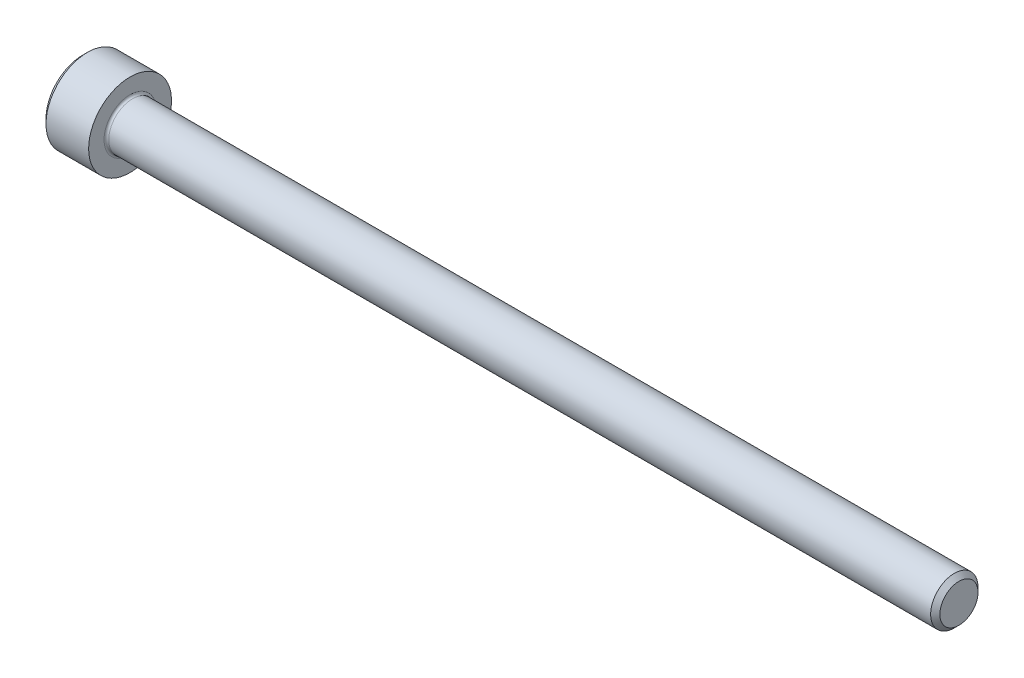
SolidWorks part; units mm, degrees
revolve "Base-Revolve" add sketch "BodySke"
sketch "BodySke" plane through (0, 0, 0) normal (0, 0, 1) x (1, 0, 0)
  line L0 (0, 0) -> (0, 3.1)
  line L1 (0.4, 3.5) -> (4, 3.5)
  line L2 (4, 3.5) -> (4, 2)
  line L3 (4, 2) -> (73.61, 2)
  line L4 (74, 1.61) -> (74, 0)
  line L5 (74, 0) -> (0, 0)
  line L6 (-31.75, 0) -> (127, 0) construction
  line L7 (0, 3.1) -> (0.4, 3.5)
  line L8 (74, 1.61) -> (73.61, 2)
  line L9 (0, -3.1) -> (0.4, -3.5) construction
  line L10 (74, -1.61) -> (73.61, -2) construction
  line L11 (4.7, 9.525) -> (4.7, 3.175) construction
  line L12 (54, 9.525) -> (54, 3.175) construction
  line L13 (24, 9.525) -> (24, 3.175) construction
  dimension "Diameter" = 4
  dimension "Head_ht" = 4
  dimension "Length" = 70
  dimension "Body_ch_ang" = 45
  dimension "Head_dia" = 7
  dimension "Head_ch_ang" = 45
  dimension "Minor_dia" = 3.22
  dimension "Advance" = 0.7
  dimension "Thread_nom" = 20
  dimension "Thread_length" = 50
  dimension "Head_ch_ht" = 0.4
cosmetic thread "ThreadCosmetic" [suppressed]
fillet "Fillet1" radius 0.2 1 edges at (4, 0, 2)
ref_plane "Plane1" through (0, 0, 0) normal (0, 0, 1) x (1, 0, 0)
ref_plane "Plane2" through (0, 0, 0) normal (0, 1, 0) x (1, 0, 0)
ref_plane "Plane3" through (0, 0, 0) normal (1, 0, 0) x (0, 0, -1)
sketch "Sketch2" plane through (0, 0, 0) normal (0, 0, 1) x (1, 0, 0)
  line L0 (0, 1.5355) -> (2, 1.5355)
  line L1 (2, 1.5355) -> (2.8865, 0)
  line L2 (-31.75, 0) -> (127, 0) construction
  line L3 (2.8865, 0) -> (0, 0)
  line L4 (0, 0) -> (0, 1.5355)
  line L5 (0, 3.1) -> (0, -3.1) construction
  line L6 (0, 0) -> (47.625, 0) construction
  line L7 (4, -3.5) -> (4, 3.5) construction
  dimension "D2" = 60
revolve "Hex-PreBroach" cut sketch "Sketch2" angle 360 about L6
sketch "Sketch3" plane through (0, 0, 0) normal (-1, 0, 0) x (0, 0.5, 0.866)
  line L0 (0.8865, 1.5355) -> (-0.8865, 1.5355)
  line L1 (-0.8865, 1.5355) -> (-1.773, 0)
  line L2 (0.8865, 1.5355) -> (1.773, 0)
  line L3 (0.8865, -1.5355) -> (1.773, 0)
  line L4 (0.8865, -1.5355) -> (-0.8865, -1.5355)
  line L5 (-0.8865, -1.5355) -> (-1.773, 0)
extrude "Hex" cut sketch "Sketch3" against normal blind 2
sketch "Sketch4" plane through (0, 0, 0) normal (-1, 0, 0) x (0, 0, 1)
  line L0 (0, 0) -> (1.7399, 0)
  line L1 (0, 0) -> (6.1484, 3.5498) construction
  line L2 (0, 0) -> (0.8699, 1.5068)
  line L3 (1.4457, 0.3947) -> (1.6607, 0.5189)
  line L4 (1.0647, 1.0546) -> (1.2797, 1.1788)
  arc A0 (1.4457, 0.3947) -> (1.0647, 1.0546) centre (0, 0) ccw
  arc A1 (1.7399, 0) -> (1.6607, 0.5189) centre (0, 0) ccw
  arc A2 (0.8699, 1.5068) -> (1.2797, 1.1788) centre (0, 0) cw
  dimension "D1" = 30
  dimension "D2" = 60
extrude "Spline" [suppressed] cut sketch "Sketch4" against normal blind 2
pattern_circular "CirPattern1" [suppressed] count 6 every 60
sketch "Sketch5" plane through (0, 0, 0) normal (0, 0, 1) x (1, 0, 0)
  line L0 (-31.75, 0) -> (127, 0) construction
  line L2 (0, 3.1) -> (0, -3.1) construction
  circle A0 centre (1.6, 0) radius 0.675
  dimension "Drilled_hole_dia" = 1.35
  dimension "Drilled_hole_loc" = 1.6
extrude "Hole" [suppressed] cut sketch "Sketch5" against normal through all and the other way through all
pattern_circular "Drilled-4" [suppressed] count 2 every 60
pattern_circular "Drilled-6" [suppressed] count 3 every 60
sketch "ThdSchSke" plane through (0, 0, 0) normal (0, 0, 1) x (1, 0, 0)
  line L0 (54, -1.61) -> (53.7269, -2)
  line L1 (54, -1.61) -> (54.2731, -2)
  line L2 (54.2731, -2) -> (54.2731, -2.5)
  line L3 (-3.175, 0) -> (5.1513, 0) construction
  line L5 (54.2731, -2.5) -> (53.7269, -2.5)
  line L6 (53.7269, -2.5) -> (53.7269, -2)
  line L7 (0, 3.1) -> (0, -3.1) construction
revolve "ThreadSchematic" [suppressed] cut sketch "ThdSchSke" angle 360 about L3
pattern_linear "ThdSchPat" [suppressed]
equation "\"D2@Sketch3\" = \"Hex_size@Sketch3\" / 2"
equation "\"D1@Sketch3\" = \"Hex_size@Sketch3\" / 2"
equation "\"D1@Sketch2\" = \"Hex_size@Sketch3\" / 2"
equation "\"D3@Sketch4\" = \"Spline_p_dim@Sketch4\" / 2"
equation "\"Thread_minor@ThreadCosmetic\"  =  \"Minor_dia@BodySke\""
equation "\"D2@CirPattern1\" = 360 / \"Num_teeth@CirPattern1\""
equation "\"Wall_thickness@Sketch2\" = \"Head_ht@BodySke\" - \"Key_eng@Hex\""
equation "\"Thread_length@ThreadCosmetic\" = ((sgn( (\"Length@BodySke\" - \"Advance@BodySke\" ) - \"Thread_nom@BodySke\" )-1)*( (\"Length@BodySke\" - \"Advance@BodySke\" ) - \"Thread_nom@BodySke\" ))/-2+ \"Thread_nom@BodySke\""
equation "\"Thread_minor@ThdSchSke\" = \"Minor_dia@BodySke\""
equation "\"Diameter@ThdSchSke\" = \"Diameter@BodySke\""
equation "\"Overcut@ThdSchSke\" = \"Diameter@BodySke\" * 1.25"
equation "\"Start@ThdSchSke\" = \"Head_ht@BodySke\" + \"Length@BodySke\" - \"Thread_length@ThreadCosmetic\"  '---Non-countersunk---"
equation "\"Num_threads@ThdSchPat\" = int( \"Thread_length@ThreadCosmetic\" / \"Advance@BodySke\" + 0.999 )  + 1"
equation "\"Advance@ThdSchPat\" = \"Thread_length@ThreadCosmetic\" /  (\"Num_threads@ThdSchPat\" - 1) 'relax it"
equation "\"Num_threads@ThdSchPat\" = \"Num_threads@ThdSchPat\" - sgn( \"Num_threads@ThdSchPat\" - 1) '---chamfered tips only---"
